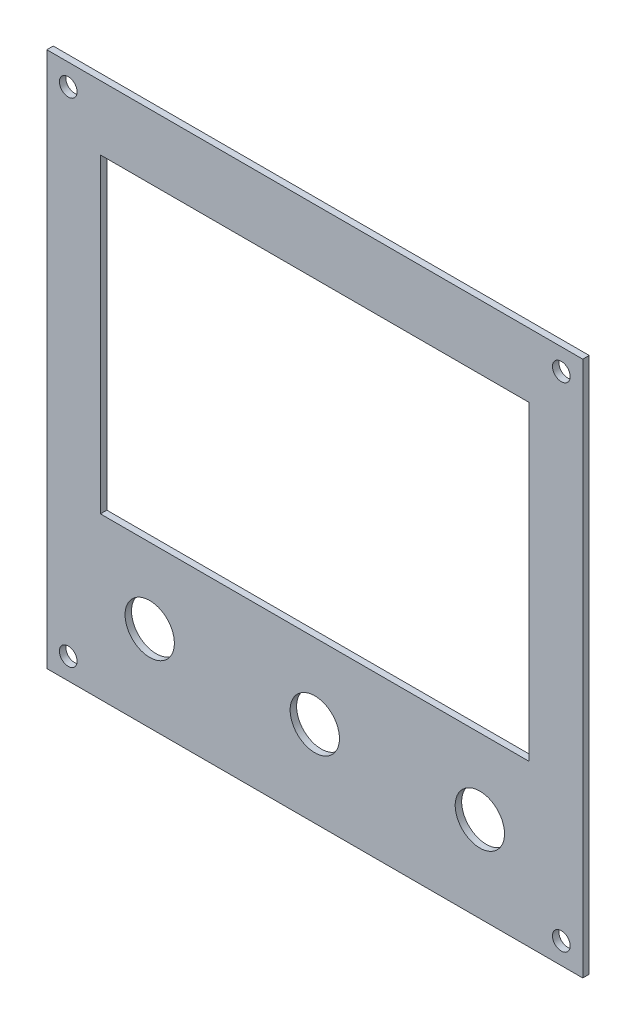
SolidWorks part; units mm, degrees
ref_plane "Front Plane" through (0, 0, 0) normal (0, 0, 1) x (1, 0, 0)
ref_plane "Top Plane" through (0, 0, 0) normal (0, 1, 0) x (1, 0, 0)
ref_plane "Right Plane" through (0, 0, 0) normal (1, 0, 0) x (0, 0, -1)
sketch "Sketch1" plane through (0, 0, 0) normal (0, 0, 1) x (1, 0, 0)
  line L1 (-100, -50) -> (100, -50)
  line L2 (-100, -50) -> (-100, 95)
  line L3 (-100, 95) -> (100, 95)
  line L4 (100, -50) -> (100, 95)
  line L7 (-125, -125) -> (125, -125)
  line L8 (-125, -125) -> (-125, 125)
  line L9 (-125, 125) -> (125, 125)
  line L10 (125, -125) -> (125, 125)
  line L11 (-125, -125) -> (125, 125) construction
  line L12 (-125, 125) -> (125, -125) construction
  circle A0 centre (-115, 115) radius 4.125
  circle A1 centre (115, 115) radius 4.125
  circle A2 centre (115, -115) radius 4.125
  circle A3 centre (-115, -115) radius 4.125
  circle A4 centre (-77, -85) radius 11.5
  circle A6 centre (0, -85) radius 11.5
  circle A7 centre (77, -85) radius 11.5
  point P0 (0, 0)
  point P6 (0, 0)
  dimension "D6" = 8.25
  dimension "D5" = 23
  dimension "D8" = 48
  dimension "D1" = 200
  dimension "D2" = 145
  dimension "D3" = 250
  dimension "D4" = 250
  dimension "D7" = 40
  dimension "D10" = 30
  dimension "D9" = 3
extrude "Boss-Extrude1" add sketch "Sketch1" along normal blind 3
